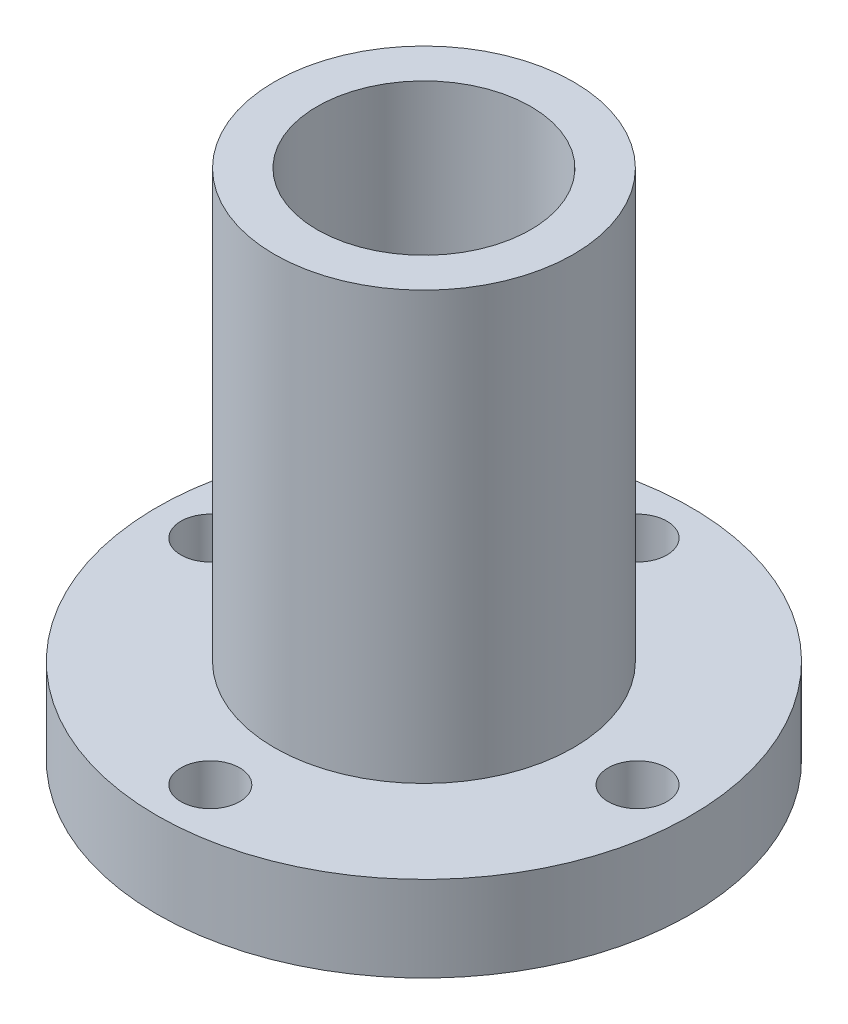
SolidWorks part; units mm, degrees
material "3.0205 (EN-AW 1200)"
ref_plane "Plan de face" through (0, 0, 0) normal (0, 0, 1) x (1, 0, 0)
ref_plane "Plan de dessus" through (0, 0, 0) normal (0, 1, 0) x (1, 0, 0)
ref_plane "Plan de droite" through (0, 0, 0) normal (1, 0, 0) x (0, 0, -1)
sketch "Esquisse1" plane through (0, 0, 0) normal (0, 1, 0) x (1, 0, 0)
  circle A0 centre (0, 0) radius 25
  dimension "D1" = 50
extrude "Boss.-Extru.1" add sketch "Esquisse1" along normal blind 8
sketch "Esquisse2" plane through (0, 8, 0) normal (0, 1, 0) x (1, 0, 0)
  circle A0 centre (0, 0) radius 14
  dimension "D1" = 28
extrude "Boss.-Extru.2" add sketch "Esquisse2" along normal blind 40
sketch "Esquisse3" plane through (0, 48, 0) normal (0, 1, 0) x (1, 0, 0)
  circle A0 centre (0, 0) radius 10
  dimension "D1" = 20
extrude "Enlèv. mat.-Extru.1" cut sketch "Esquisse3" against normal through all both and the other way through all
sketch "Esquisse4" plane through (0, 8, 0) normal (0, 1, 0) x (1, 0, 0)
  line L0 (0, 53.0563) -> (0, 0) construction
  circle A0 centre (0, 0) radius 20 construction
  circle A1 centre (0, 20) radius 2.75
  circle A2 centre (20, 0) radius 2.75
  circle A3 centre (0, -20) radius 2.75
  circle A4 centre (-20, 0) radius 2.75
  point P6 (20, 0)
  point P15 (0, 0)
  dimension "D1" = 40
  dimension "D2" = 5.5
  dimension "D3" = 4
extrude "Enlèv. mat.-Extru.2" cut sketch "Esquisse4" against normal through all both and the other way through all
